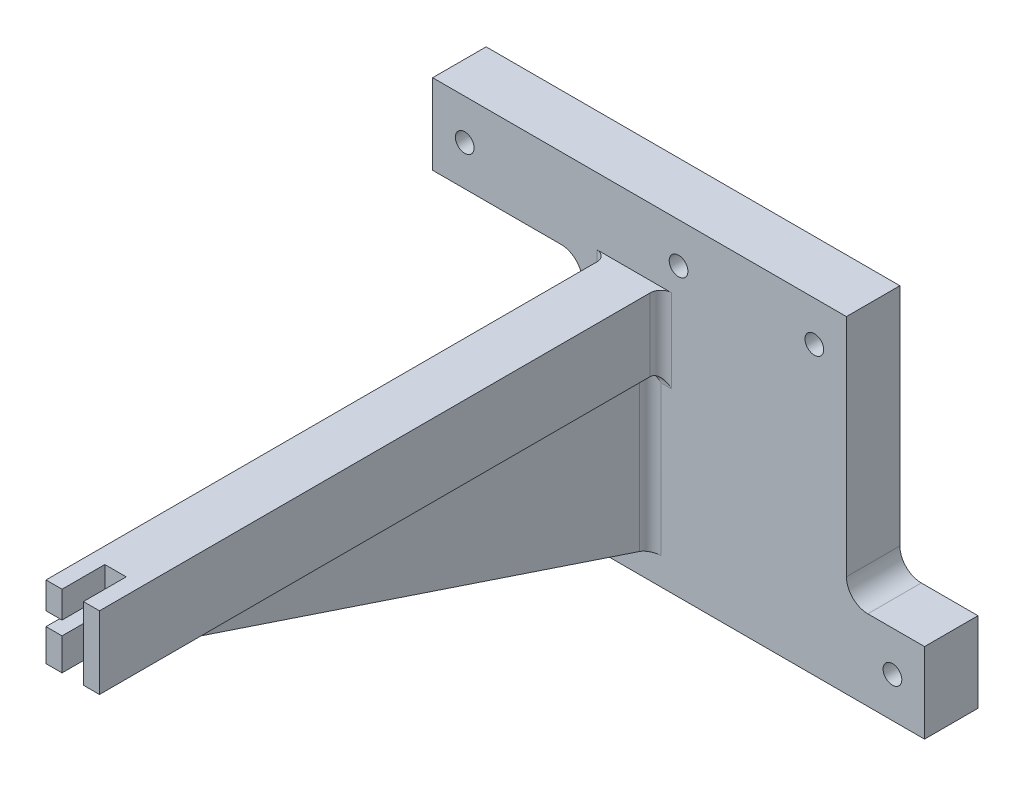
SolidWorks part; units mm, degrees
ref_plane "Front Plane" through (0, 0, 0) normal (0, 0, 1) x (1, 0, 0)
ref_plane "Top Plane" through (0, 0, 0) normal (0, 1, 0) x (1, 0, 0)
ref_plane "Right Plane" through (0, 0, 0) normal (1, 0, 0) x (0, 0, -1)
sketch "Sketch1" plane through (0, 0, 0) normal (0, 0, 1) x (1, 0, 0)
  line L0 (-45.99, 7.5) -> (-45.99, -7.5)
  line L1 (-45.99, -7.5) -> (-17.99, -7.5)
  line L2 (-17.99, -7.5) -> (-17.99, -53.64)
  line L3 (-17.99, -53.64) -> (46, -53.64)
  line L4 (46, -53.64) -> (46, -38.64)
  line L5 (46, -38.64) -> (31.39, -38.64)
  line L6 (31.39, -38.64) -> (31.39, 7.5)
  line L7 (31.39, 7.5) -> (-45.99, 7.5)
  circle A0 centre (0, 0) radius 1.75
  circle A1 centre (25.39, 0) radius 1.75
  circle A2 centre (-39.99, 0) radius 1.75
  circle A3 centre (40, -46.14) radius 1.75
  point P11 (-45.99, 0)
  point P18 (46, -46.14)
  dimension "D6" = 3.5
  dimension "D1" = 39.99
  dimension "D2" = 25.39
  dimension "D3" = 14.61
  dimension "D4" = 46.14
  dimension "D5" = 6
  dimension "D7" = 6
  dimension "D8" = 6
  dimension "D9" = 15
  dimension "D10" = 15
  dimension "D11" = 28
extrude "Boss-Extrude1" add sketch "Sketch1" along normal blind 10
sketch "Sketch2" plane through (0, 0, 10) normal (0, 0, 1) x (1, 0, 0)
  line L0 (-13.3, -5) -> (-3.3, -5)
  line L1 (-3.3, -5) -> (-3.3, -18.56)
  line L2 (-3.3, -18.56) -> (-13.3, -18.56)
  line L3 (-13.3, -18.56) -> (-13.3, -12.56)
  line L4 (-13.3, -12.56) -> (-8.3, -12.56)
  line L5 (-8.3, -12.56) -> (-8.3, -10)
  line L6 (-8.3, -10) -> (-13.3, -10)
  line L7 (-13.3, -10) -> (-13.3, -5)
  circle A0 centre (0, 0) radius 1.75 construction
  dimension "D1" = 6
  dimension "D2" = 5
  dimension "D3" = 2.56
  dimension "D4" = 10
  dimension "D5" = 5
  dimension "D6" = 10
  dimension "D7" = 13.3
extrude "Boss-Extrude2" add sketch "Sketch2" along normal blind 105
ref_plane "Plane1" through (-8.3, 0, 0) normal (1, 0, 0) x (0, 0, -1)
sketch "Sketch3" plane through (-8.3, 0, 0) normal (1, 0, 0) x (0, 0, -1)
  line L0 (-10, -48.56) -> (-100, -18.56)
  line L1 (-115, -18.56) -> (-10, -18.56) construction
  line L2 (-10, 1.75) -> (-10, -1.75) construction
  dimension "D1" = 90
  dimension "D2" = 30
rib "Rib1" sketch "Sketch3" sketch "Sketch3" thickness 6 extrusion direction parallel to sketch draft on no parameters "D1"=6
fillet "Fillet1" radius 2 7 edges at (-13.3, -7.5, 10) (-13.3, -15.56, 10) (-12.3, -18.56, 10) (-11.3, -33.56, 10) (-3.3, -11.78, 10) (-4.3, -18.56, 10) (-5.3, -33.56, 10)
fillet "Fillet2" radius 4 3 edges at (31.39, -38.64, 5) (-17.99, -53.64, 5) (-17.99, -7.5, 5)
sketch "Sketch4" plane through (0, 0, 115) normal (0, 0, 1) x (1, 0, 0)
  line L0 (-13.3, -18.56) -> (-3.3, -18.56) construction
  line L1 (-10.3, -18.56) -> (-6.3, -18.56)
  line L2 (-10.3, -18.56) -> (-10.3, -5)
  line L3 (-10.3, -5) -> (-6.3, -5)
  line L4 (-6.3, -18.56) -> (-6.3, -5)
  line L5 (-3.3, -5) -> (-13.3, -5) construction
  line L6 (-3.3, -18.56) -> (-3.3, -5) construction
  line L7 (-13.3, -12.56) -> (-13.3, -18.56) construction
  dimension "D1" = 3
  dimension "D2" = 3
extrude "Cut-Extrude1" cut sketch "Sketch4" against normal blind 8
